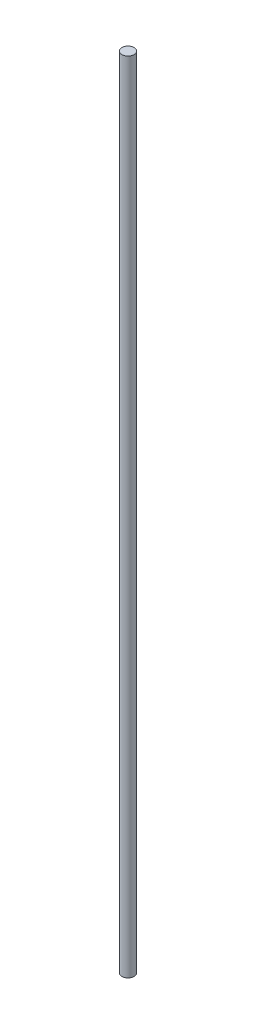
SolidWorks part; units mm, degrees
ref_plane "Płaszczyzna przednia" through (0, 0, 0) normal (0, 0, 1) x (1, 0, 0)
ref_plane "Płaszczyzna górna" through (0, 0, 0) normal (0, 1, 0) x (1, 0, 0)
ref_plane "Płaszczyzna prawa" through (0, 0, 0) normal (1, 0, 0) x (0, 0, -1)
sketch "Szkic1" plane through (0, 0, 0) normal (0, 1, 0) x (1, 0, 0)
  circle A0 centre (0, 0) radius 4
  dimension "D1" = 8
extrude "Dodanie-wyciągnięcie1" add sketch "Szkic1" along normal blind 520
cosmetic thread "Oznaczenie gwintu1" parameters "D2"=7
